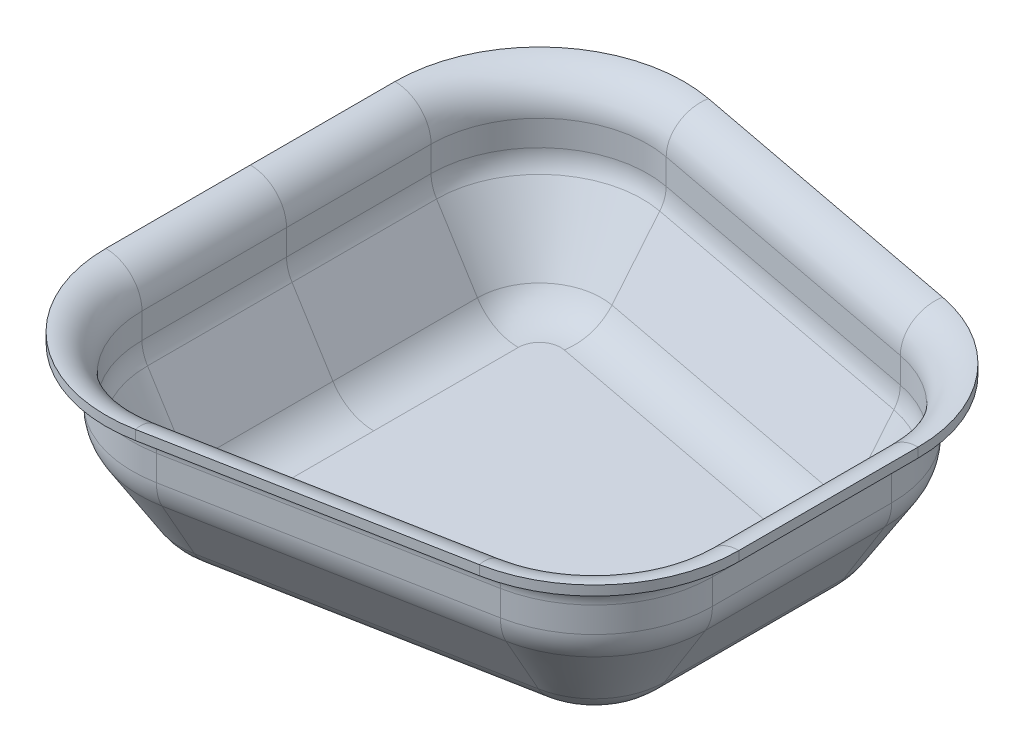
SolidWorks part; units mm, degrees
material "Silicon"
ref_plane "Front" through (0, 0, 0) normal (0, 0, 1) x (1, 0, 0)
ref_plane "Top" through (0, 0, 0) normal (0, 1, 0) x (1, 0, 0)
ref_plane "Right" through (0, 0, 0) normal (1, 0, 0) x (0, 0, -1)
sketch "Sketch2" plane through (0, 0, 0) normal (0, 0, 1) x (1, 0, 0)
  line L0 (-66.675, 37.465) -> (-66.675, 30.734)
  line L1 (-65.22, 25.6742) -> (-54.448, 8.4936)
  line L2 (-43.688, 2.54) -> (0, 2.54) construction
  line L4 (-69.215, 37.465) -> (-69.215, 30.734)
  line L7 (-67.372, 24.325) -> (-56.5999, 7.1444)
  line L8 (-43.688, 0) -> (0, 0) construction
  line L11 (0, 0) -> (0, 2.54) construction
  line L12 (-43.688, 0) -> (0, 0) construction
  line L13 (-43.688, 2.54) -> (-43.688, 0)
  line L14 (-76.2, 44.45) -> (-76.2, 46.99)
  line L15 (-76.2, 46.99) -> (-66.675, 46.99) construction
  line L16 (-66.675, 46.99) -> (-66.675, 37.465) construction
  arc A0 (-76.2, 46.99) -> (-66.675, 37.465) centre (-76.2, 37.465) cw
  arc A1 (-66.675, 30.734) -> (-65.22, 25.6742) centre (-57.15, 30.734) ccw
  arc A2 (-54.448, 8.4936) -> (-43.688, 2.54) centre (-43.688, 15.24) ccw
  arc A3 (-76.2, 44.45) -> (-69.215, 37.465) centre (-76.2, 37.465) cw
  arc A4 (-69.215, 30.734) -> (-67.372, 24.325) centre (-57.15, 30.734) ccw
  arc A5 (-56.5999, 7.1444) -> (-43.688, 0) centre (-43.688, 15.24) ccw
  point P10 (-43.688, 4.8916)
  point P12 (0, 0)
  dimension "D1" = 9.525
  dimension "D2" = 9.525
  dimension "D3" = 12.7
  dimension "D4" = 16.256
  dimension "D5" = 31.75
  dimension "D6" = 32.512
  dimension "D7" = 2.54
  dimension "D8" = 76.2
sketch "Sketch3" plane through (0, 0, 0) normal (0, 1, 0) x (1, 0, 0)
  line L3 (-30.9882, 75.5304) -> (45.2118, 61.0524)
  line L4 (-76.2, 38.1) -> (-76.2, -38.1)
  line L6 (76.2, 23.622) -> (76.2, -23.622)
  line L7 (-76.2, 0) -> (76.2, 0) construction
  line L8 (-30.9882, -75.5304) -> (45.2118, -61.0524)
  arc A0 (-76.2, 38.1) -> (-30.9882, 75.5304) centre (-38.1, 38.1) cw
  arc A1 (45.2118, 61.0524) -> (76.2, 23.622) centre (38.1, 23.622) cw
  arc A2 (45.2118, -61.0524) -> (76.2, -23.622) centre (38.1, -23.622) ccw
  arc A3 (-76.2, -38.1) -> (-30.9882, -75.5304) centre (-38.1, -38.1) ccw
  point P4 (-87.2597, 39.4161)
  point P5 (45.2118, 45.3082)
  point P6 (-37.6466, 72.8028)
  point P20 (17.8795, 74.5656)
  dimension "D4" = 38.1
  dimension "D1" = 76.2
  dimension "D2" = 38.1
  dimension "D3" = 23.622
  dimension "D5" = 76.2
  dimension "D6" = 76.2
sweep "Sweep1" add profiles "Sketch2" path "Sketch3"
sketch "Sketch5" plane through (0, 0, 0) normal (0, 1, 0) x (1, 0, 0)
  line L0 (43.688, 23.622) -> (43.688, -23.622) construction
  line L1 (39.1431, -29.1118) -> (-37.0569, -43.5898) construction
  line L2 (-43.688, -38.1) -> (-43.688, 0) construction
  line L3 (-43.688, 0) -> (-43.688, 38.1) construction
  line L4 (-37.0569, 43.5898) -> (39.1431, 29.1118) construction
  line L5 (43.688, 23.622) -> (43.688, -23.622)
  line L6 (39.1431, -29.1118) -> (-37.0569, -43.5898)
  line L7 (-43.688, -38.1) -> (-43.688, 0)
  line L8 (-43.688, 0) -> (-43.688, 38.1)
  line L9 (-37.0569, 43.5898) -> (39.1431, 29.1118)
  arc A0 (43.688, 23.622) -> (39.1431, 29.1118) centre (38.1, 23.622) ccw construction
  arc A1 (39.1431, -29.1118) -> (43.688, -23.622) centre (38.1, -23.622) ccw construction
  arc A2 (-43.688, -38.1) -> (-37.0569, -43.5898) centre (-38.1, -38.1) ccw construction
  arc A3 (-37.0569, 43.5898) -> (-43.688, 38.1) centre (-38.1, 38.1) ccw construction
  arc A4 (43.688, 23.622) -> (39.1431, 29.1118) centre (38.1, 23.622) ccw
  arc A5 (39.1431, -29.1118) -> (43.688, -23.622) centre (38.1, -23.622) ccw
  arc A6 (-43.688, -38.1) -> (-37.0569, -43.5898) centre (-38.1, -38.1) ccw
  arc A7 (-37.0569, 43.5898) -> (-43.688, 38.1) centre (-38.1, 38.1) ccw
extrude "Boss-Extrude2" add sketch "Sketch5" along normal blind 2.54
